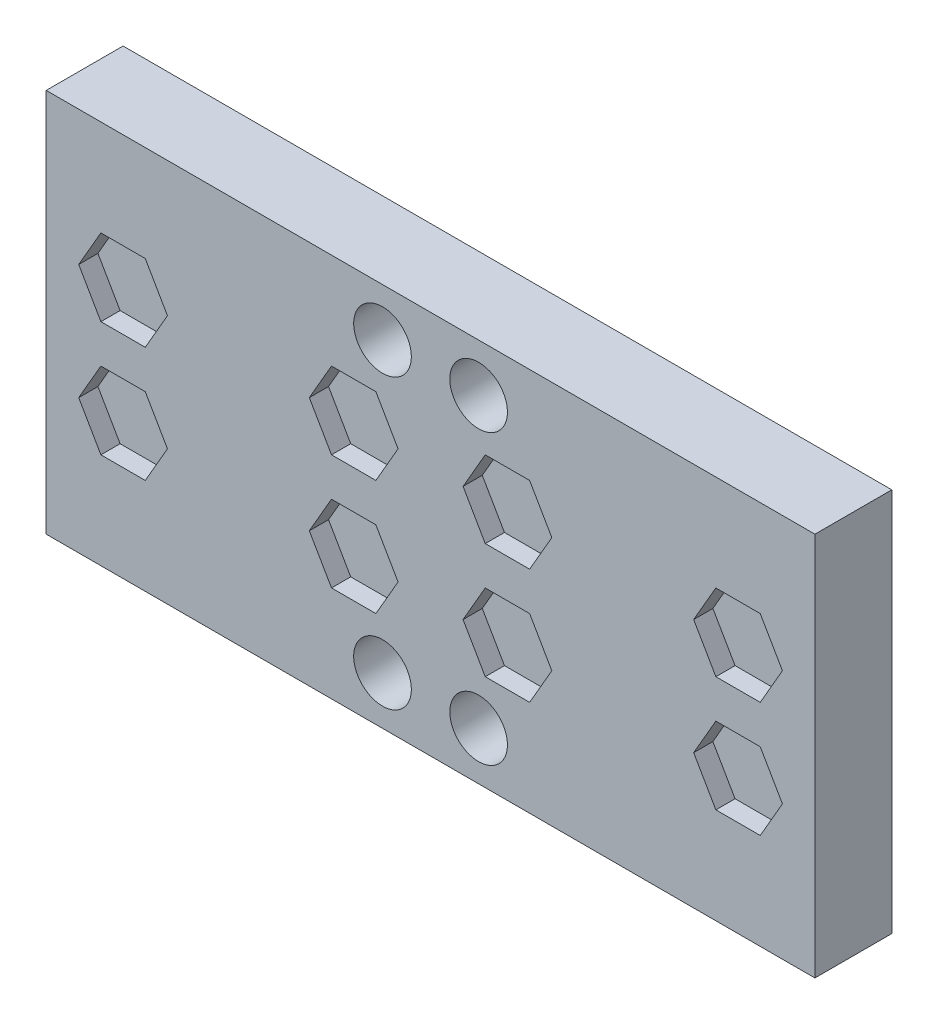
SolidWorks part; units mm, degrees
material "AISI 1020"
ref_plane "Front Plane" through (0, 0, 0) normal (0, 0, 1) x (1, 0, 0)
ref_plane "Top Plane" through (0, 0, 0) normal (0, 1, 0) x (1, 0, 0)
ref_plane "Right Plane" through (0, 0, 0) normal (1, 0, 0) x (0, 0, -1)
sketch "Sketch1" plane through (0, 0, 0) normal (0, 0, 1) x (1, 0, 0)
  line L0 (87.5, 37.5) -> (100, 37.5) construction
  line L1 (0, 0) -> (100, 0)
  line L2 (0, 0) -> (0, 50)
  line L3 (0, 50) -> (100, 50)
  line L4 (100, 0) -> (100, 50)
  line L5 (87.5, 37.5) -> (87.5, 50) construction
  circle A0 centre (87.5, 37.5) radius 7.5
  dimension "D4" = 15
  dimension "D1" = 50
  dimension "D2" = 100
  dimension "D3" = 12.5
extrude "Boss-Extrude1" add sketch "Sketch1" along normal blind 10
sketch "Sketch2" plane through (0, 0, 10) normal (0, 0, 1) x (1, 0, 0)
  line L0 (0, 0) -> (100, 0) construction
  line L1 (25.7735, 25) -> (14.2265, 25)
  line L2 (14.2265, 25) -> (8.453, 15)
  line L3 (8.453, 15) -> (14.2265, 5)
  line L4 (14.2265, 5) -> (25.7735, 5)
  line L5 (25.7735, 5) -> (31.547, 15)
  line L6 (31.547, 15) -> (25.7735, 25)
  line L7 (0, 50) -> (0, 0) construction
  circle A0 centre (20, 15) radius 10 construction
  dimension "D3" = 20
  dimension "D1" = 25
  dimension "D2" = 20
extrude "Cut-Extrude1" cut sketch "Sketch2" against normal blind 5
ref_plane "Plane1" through (50, 0, 0) normal (-1, 0, 0) x (0, 0, 1)
mirror "Mirror1" about plane through (50, 0, 0) normal (-1, 0, 0) of "Cut-Extrude1"
mirror "Mirror3" about plane through (0, 0, 10) normal (0, 1, 0) of bodies 103
mirror "Mirror4" about plane through (100, 0, 10) normal (-1, 0, 0) of bodies 105
mirror "Mirror5" about plane through (0, 0, 0) normal (0, 0, -1) of bodies 106
equation "\"D2@Sketch1\"=\"D1@Sketch1\"*2"
